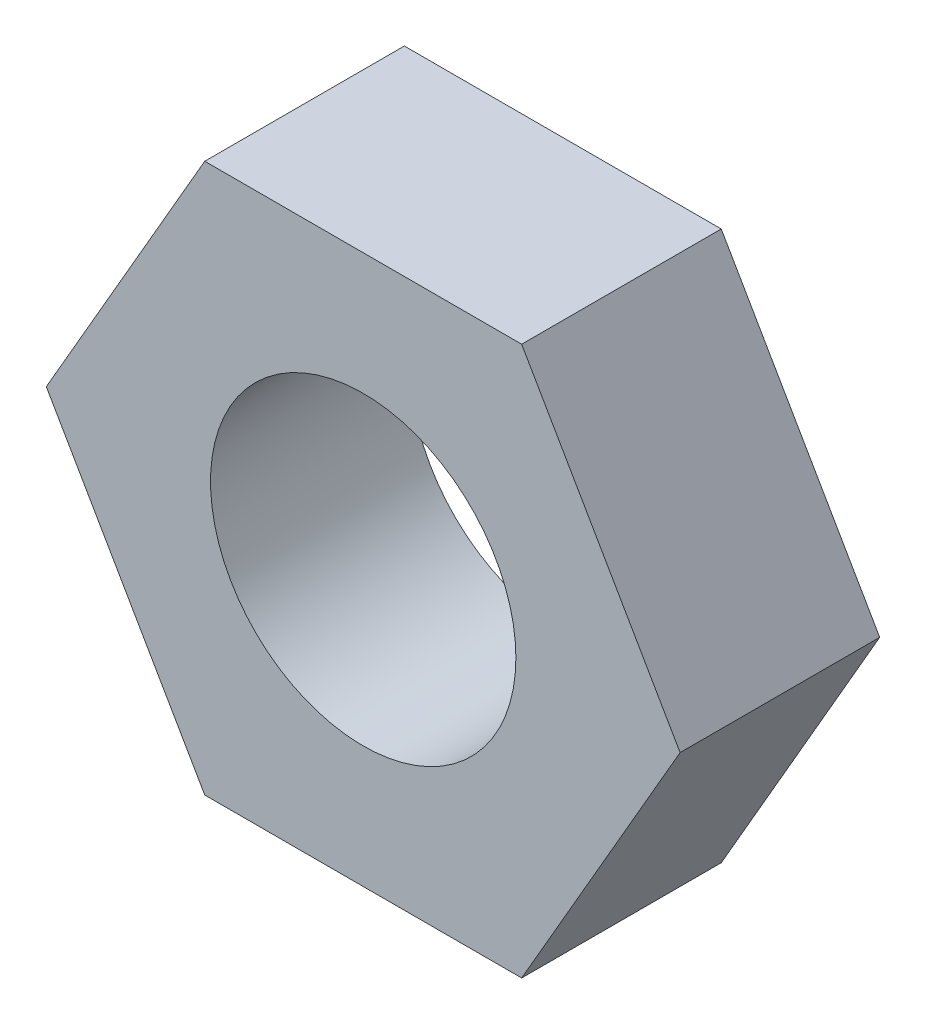
SolidWorks part; units mm, degrees
ref_plane "Front Plane" through (0, 0, 0) normal (0, 0, 1) x (1, 0, 0)
ref_plane "Top Plane" through (0, 0, 0) normal (0, 1, 0) x (1, 0, 0)
ref_plane "Right Plane" through (0, 0, 0) normal (1, 0, 0) x (0, 0, -1)
sketch "S01 - Small hex locking nut" plane through (0, 0, 0) normal (0, 0, 1) x (1, 0, 0)
  line L0 (3.1754, 0) -> (1.5877, 2.75)
  line L1 (1.5877, 2.75) -> (-1.5877, 2.75)
  line L2 (-1.5877, 2.75) -> (-3.1754, 0)
  line L3 (-3.1754, 0) -> (-1.5877, -2.75)
  line L4 (-1.5877, -2.75) -> (1.5877, -2.75)
  line L5 (1.5877, -2.75) -> (3.1754, 0)
  circle A0 centre (0, 0) radius 1.53
  dimension "D1" = 3.06
  dimension "D2" = 1.5877
  dimension "D3" = 3.1754
  dimension "D4" = 1.5877
  dimension "D5" = 3.1754
  dimension "D6" = 2.75
  dimension "D7" = 2.75
extrude "01 - Small hex locking nut" add sketch "S01 - Small hex locking nut" along normal blind 2
